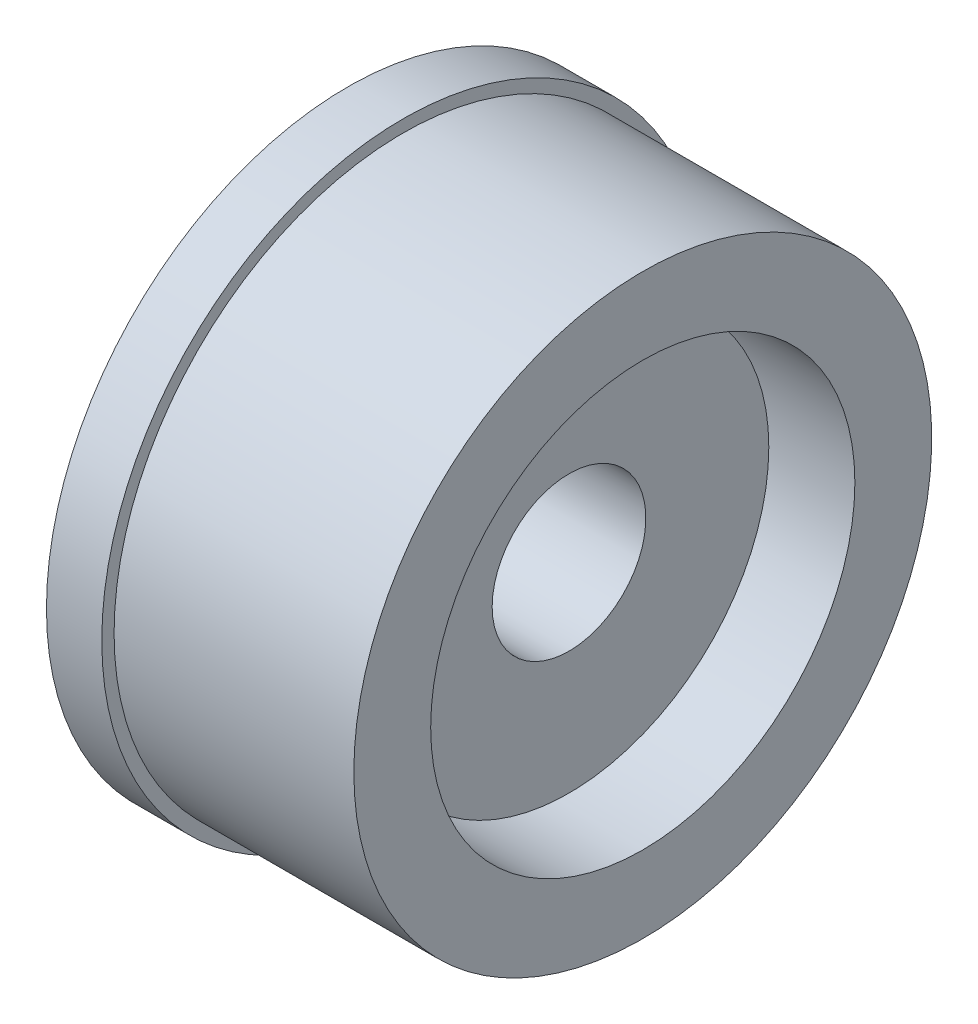
SolidWorks part; units mm, degrees
ref_plane "Ön Düzlem" through (0, 0, 0) normal (0, 0, 1) x (1, 0, 0)
ref_plane "Üst Düzlem" through (0, 0, 0) normal (0, 1, 0) x (1, 0, 0)
ref_plane "Sağ Düzlem" through (0, 0, 0) normal (1, 0, 0) x (0, 0, -1)
sketch "Çizim1" plane through (0, 0, 0) normal (0, 0, 1) x (1, 0, 0)
  line L0 (0, 0) -> (31.8851, 0) construction
  line L5 (0, 6.25) -> (21, 6.25)
  line L6 (0, 6.25) -> (0, 10.25)
  line L7 (3, 16.25) -> (21, 16.25)
  line L8 (21, 6.25) -> (21, 16.25)
  line L9 (0, 10.25) -> (3, 16.25)
  line L10 (7.5, 24.5) -> (7.5, 23.5)
  line L11 (3, 17.25) -> (27, 17.25)
  line L12 (3, 17.25) -> (3, 24.5)
  line L13 (3, 24.5) -> (7.5, 24.5)
  line L14 (27, 17.25) -> (27, 23.5)
  line L15 (7.5, 23.5) -> (27, 23.5)
  dimension "D1" = 6.25
  dimension "D2" = 21
  dimension "D3" = 4
  dimension "D4" = 3
  dimension "D5" = 10
  dimension "D6" = 24
  dimension "D7" = 4.5
  dimension "D8" = 7.25
  dimension "D9" = 1
  dimension "D10" = 1
revolve "Döndür1" add sketch "Çizim1" angle 360 about L0
